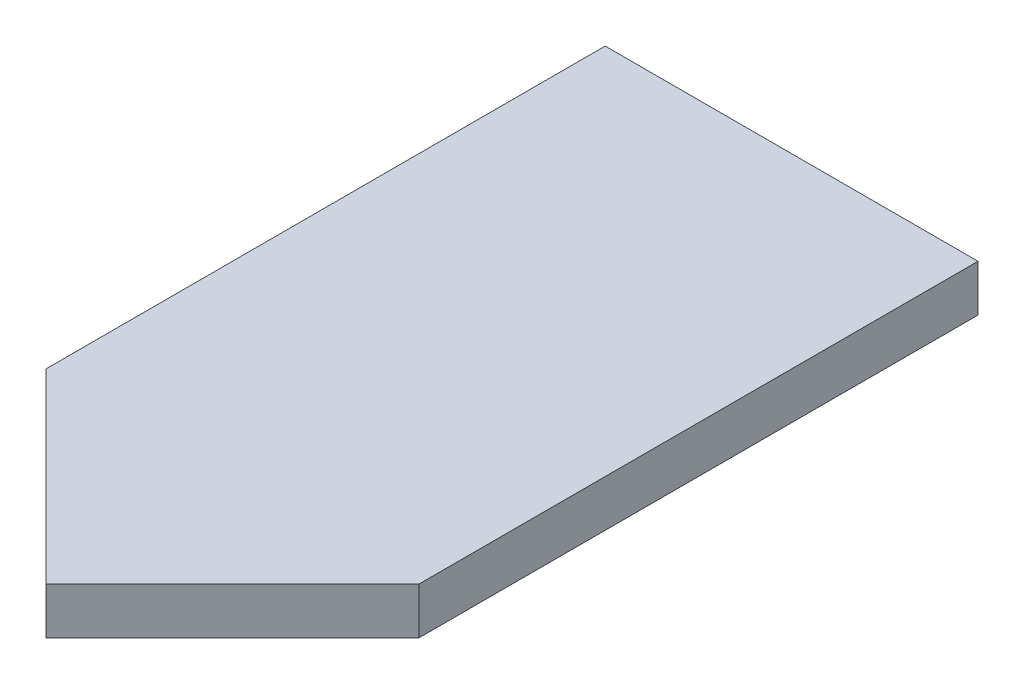
SolidWorks part; units mm, degrees
material "Glass"
ref_plane "Front Plane" through (0, 0, 0) normal (0, 0, 1) x (1, 0, 0)
ref_plane "Top Plane" through (0, 0, 0) normal (0, 1, 0) x (1, 0, 0)
ref_plane "Right Plane" through (0, 0, 0) normal (1, 0, 0) x (0, 0, -1)
sketch "Sketch2" plane through (0, 0, 0) normal (0, 1, 0) x (1, 0, 0)
  line L0 (-6.35, 0) -> (6.35, 0)
  line L1 (6.35, 0) -> (6.35, -19.05)
  line L2 (6.35, -19.05) -> (0, -25.4)
  line L3 (0, -25.4) -> (0, 0) construction
  line L4 (-6.35, -19.05) -> (0, -25.4)
  line L5 (-6.35, 0) -> (-6.35, -19.05)
  dimension "D1" = 6.35
  dimension "D2" = 19.05
  dimension "D3" = 25.4
extrude "Boss-Extrude1" add sketch "Sketch2" along normal blind 1.5875
